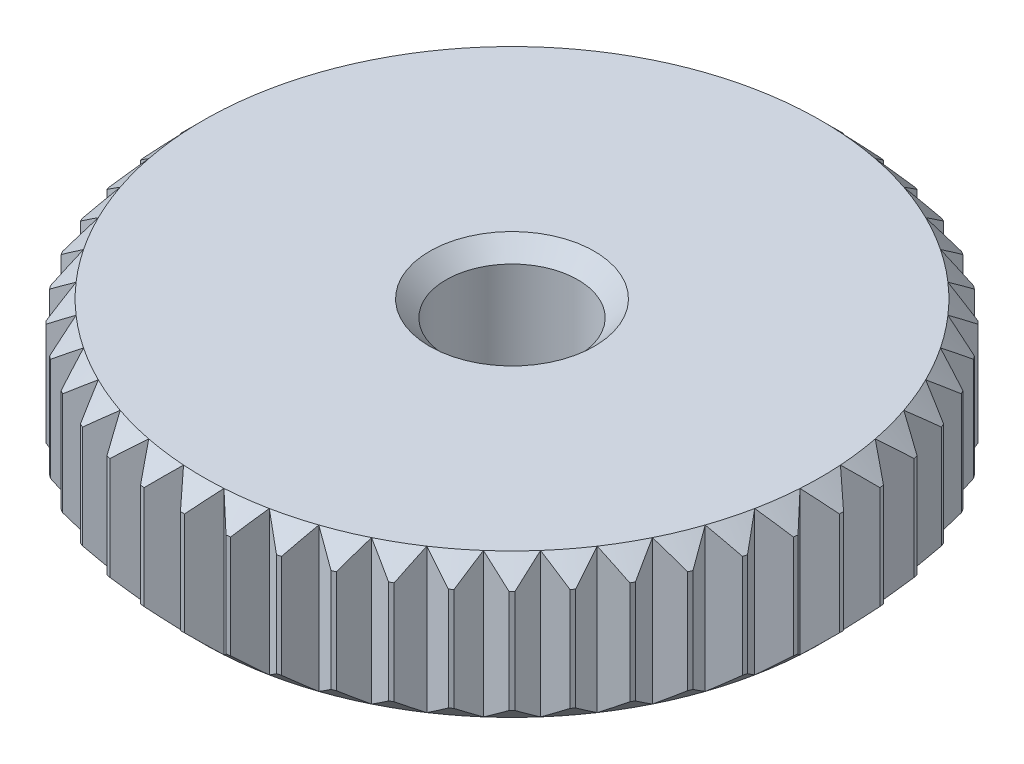
SolidWorks part; units mm, degrees
ref_plane "Front" through (0, 0, 0) normal (0, 0, 1) x (1, 0, 0)
ref_plane "Top" through (0, 0, 0) normal (0, 1, 0) x (1, 0, 0)
ref_plane "Right" through (0, 0, 0) normal (1, 0, 0) x (0, 0, -1)
sketch "Sketch6" plane through (0, 0, 0) normal (1, 0, 0) x (0, 0, -1)
  line L0 (-1.6, 1.35) -> (-2, 1.75)
  line L1 (-2, 1.75) -> (-7.5, 1.75)
  line L2 (-7.5, 1.75) -> (-8, 1.25)
  line L3 (-8, 1.25) -> (-8, -1.25)
  line L4 (-8, -1.25) -> (-7.5, -1.75)
  line L5 (-7.5, -1.75) -> (-4.5, -1.75)
  line L6 (-4, -2.25) -> (-2, -2.25)
  line L7 (-2, -2.25) -> (-1.6, -1.85)
  line L8 (-1.6, -1.85) -> (-1.6, 1.35)
  line L9 (0, 6.2494) -> (0, 0) construction
  line L10 (0, 0) -> (6.9905, 0) construction
  arc A0 (-4.5, -1.75) -> (-4, -2.25) centre (-4.5, -2.25) cw
  dimension "D7" = 0.5
  dimension "D1" = 3.5
  dimension "D2" = 3.2
  dimension "D3" = 16
  dimension "D4" = 45
  dimension "D5" = 0.4
  dimension "D6" = 0.5
  dimension "D8" = 2.9
revolve "Revolve1" add sketch "Sketch6" angle 360 about L9
cosmetic thread "Cosmetic Thread1" parameters "D1"=4, "D2"=4
sketch "Sketch7" plane through (0, 1.75, 0) normal (0, 1, 0) x (1, 0, 0)
  line L0 (0, 0) -> (0, 10.8975) construction
  line L1 (0.05, 7.9998) -> (0.4905, 7.4839)
  line L2 (0.4905, 7.4839) -> (0.9946, 7.9379)
  line L3 (0, 0) -> (1.4387, 10.928) construction
  circle A0 centre (0, 0) radius 8 construction
  circle A1 centre (0, 0) radius 7.5 construction
  arc A2 (0.9946, 7.9379) -> (0.05, 7.9998) centre (0, 0) ccw
  dimension "D1" = 7.5
  dimension "D2" = 0.05
  dimension "D3" = 0.05
extrude "Cut-Extrude1" cut sketch "Sketch7" against normal through all
pattern_circular "CirPattern1" count 48 over 360 about axis through (0, 0, 0) along (0, 1, 0) of "Cut-Extrude1"
